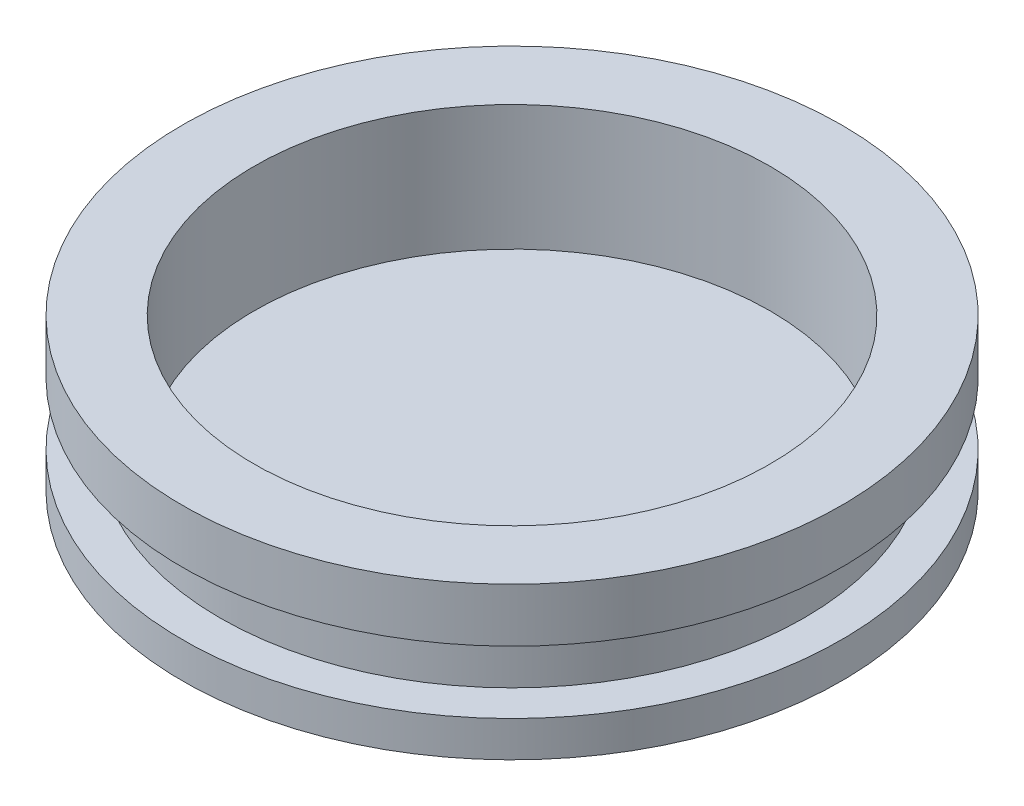
SolidWorks part; units mm, degrees
material "AISI 1020"
ref_plane "Plano frontal" through (0, 0, 0) normal (0, 0, 1) x (1, 0, 0)
ref_plane "Plano superior" through (0, 0, 0) normal (0, 1, 0) x (1, 0, 0)
ref_plane "Plano direito" through (0, 0, 0) normal (1, 0, 0) x (0, 0, -1)
sketch "Esboço1" plane through (0, 0, 0) normal (0, 0, 1) x (1, 0, 0)
  line L0 (0, 0) -> (-14.42, 0)
  line L1 (-14.42, 0) -> (-14.42, 7)
  line L2 (-14.42, 7) -> (-18.42, 7)
  line L3 (-18.42, 7) -> (-18.42, -1.5)
  line L4 (-18.42, -1.5) -> (0, -1.5)
  line L5 (0, -1.5) -> (0, 0)
  line L6 (-18.42, 4) -> (-16.32, 4)
  line L7 (-16.32, 4) -> (-16.32, 0.5)
  line L8 (-16.32, 0.5) -> (-18.42, 0.5)
  line L9 (0, -1.5) -> (0, 21.5232) construction
  dimension "D1" = 1.5
  dimension "D2" = 4
  dimension "D3" = 2.1
  dimension "D4" = 18.42
  dimension "D5" = 3.5
  dimension "D6" = 7
  dimension "D7" = 3
revolve "Revolução1" add sketch "Esboço1" angle 360 about L9
